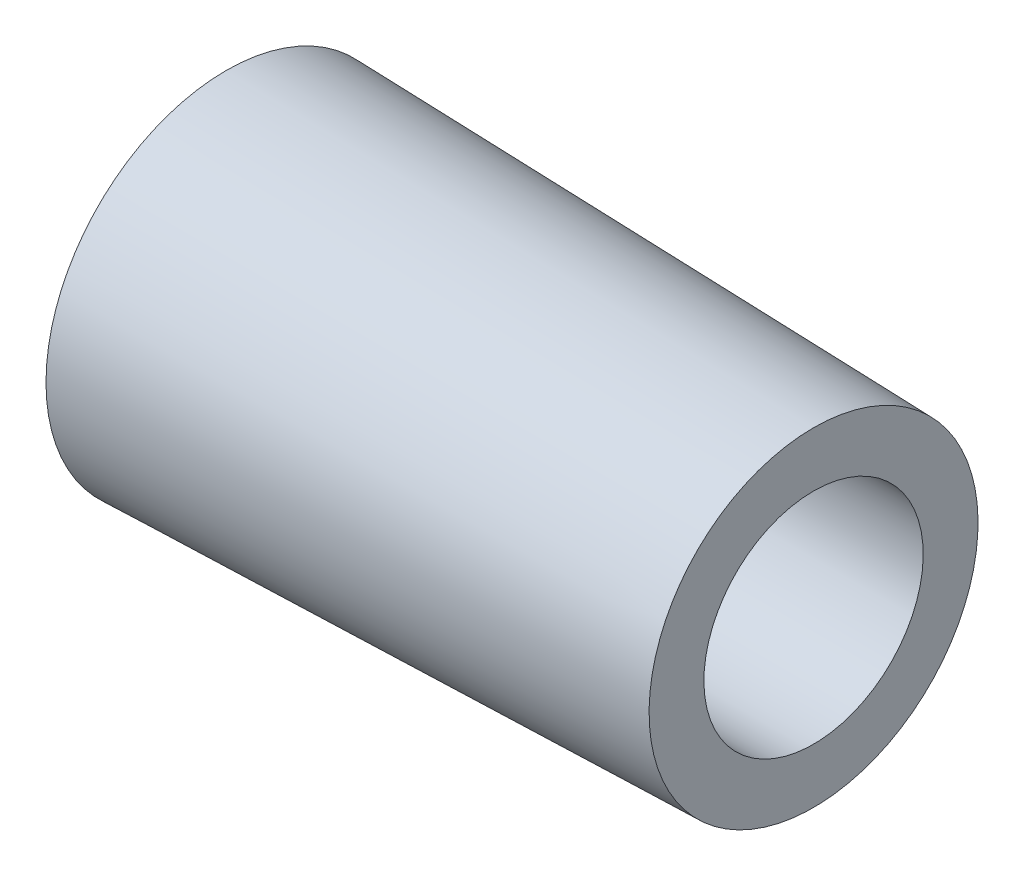
SolidWorks part; units mm, degrees
ref_plane "Front Plane" through (0, 0, 0) normal (0, 0, 1) x (1, 0, 0)
ref_plane "Top Plane" through (0, 0, 0) normal (0, 1, 0) x (1, 0, 0)
ref_plane "Right Plane" through (0, 0, 0) normal (1, 0, 0) x (0, 0, -1)
sketch "Sketch1" plane through (0, 0, 0) normal (0, 0, 1) x (1, 0, 0)
  line L0 (0, 0) -> (4000, 0) construction
  line L1 (1900, 280) -> (1900, 460)
  line L2 (1900, 460) -> (3400, 420)
  line L3 (3400, 420) -> (3400, 280)
  line L4 (3400, 280) -> (1900, 280)
revolve "Revolve1" add sketch "Sketch1" angle 360 about L0
